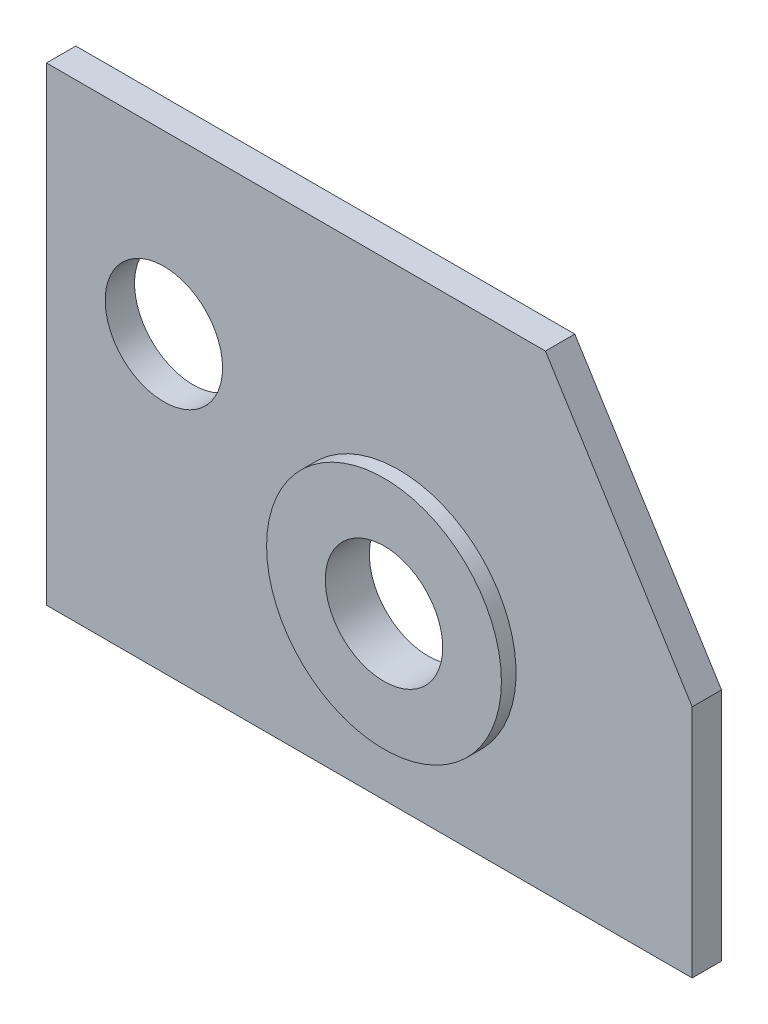
SolidWorks part; units mm, degrees
ref_plane "Front Plane" through (0, 0, 0) normal (0, 0, 1) x (1, 0, 0)
ref_plane "Top Plane" through (0, 0, 0) normal (0, 1, 0) x (1, 0, 0)
ref_plane "Right Plane" through (0, 0, 0) normal (1, 0, 0) x (0, 0, -1)
sketch "Sketch1" plane through (0, 0, 0) normal (0, 0, 1) x (1, 0, 0)
  line L1 (0, 0) -> (139.7, 0)
  line L2 (0, 0) -> (0, 101.6)
  line L3 (0, 101.6) -> (139.7, 101.6)
  line L4 (139.7, 0) -> (139.7, 101.6)
  dimension "D1" = 101.6
  dimension "D2" = 139.7
extrude "Boss-Extrude1" add sketch "Sketch1" along normal blind 6.35
sketch "Sketch2" plane through (0, 0, 6.35) normal (0, 0, 1) x (1, 0, 0)
  line L0 (107.95, 101.6) -> (139.7, 50.8)
  line L1 (139.7, 101.6) -> (0, 101.6) construction
  line L2 (139.7, 0) -> (139.7, 101.6) construction
  line L3 (0, 101.6) -> (0, 0) construction
  line L4 (0, 0) -> (139.7, 0) construction
  dimension "D1" = 107.95
  dimension "D2" = 50.8
extrude "Cut-Extrude1" cut sketch "Sketch2" against normal through all and the other way through all
hole_wizard "1 (1) Diameter Hole1" positions "Sketch3" profile "Sketch4" hole size "1" standard "ANSI Inch" end condition through all
sketch "Sketch3" plane through (0, 0, 6.35) normal (0, 0, 1) x (1, 0, 0)
  line L0 (0, 101.6) -> (0, 0) construction
  line L1 (0, 0) -> (139.7, 0) construction
  point P0 (25.4, 63.5)
  dimension "D1" = 25.4
  dimension "D2" = 63.5
sketch "Sketch4" plane through (25.4, 63.5, 6.35) normal (1, 0, 0) x (0, -1, 0)
  line L0 (0, 0) -> (0, 6.35)
  line L1 (0, 6.35) -> (12.7, 6.35)
  line L2 (12.7, 6.35) -> (12.7, 0)
  line L5 (12.7, 0) -> (0, 0)
  line L11 (0, -6.35) -> (0, 107.95) construction
  dimension "Thru Hole Dia." = 25.4
  dimension "Thru Hole Depth" = 6.35
sketch "Sketch5" plane through (0, 0, 6.35) normal (0, 0, 1) x (1, 0, 0)
  line L0 (0, 101.6) -> (0, 0) construction
  line L1 (0, 0) -> (139.7, 0) construction
  circle A0 centre (76.2, 38.1) radius 25.4
  dimension "D1" = 50.8
  dimension "D2" = 76.2
  dimension "D3" = 38.1
extrude "Boss-Extrude2" add sketch "Sketch5" along normal blind 3.175
sketch "Sketch6" plane through (0, 0, 9.525) normal (0, 0, 1) x (1, 0, 0)
  circle A0 centre (76.2, 38.1) radius 12.7
extrude "Cut-Extrude2" cut sketch "Sketch6" against normal through all
